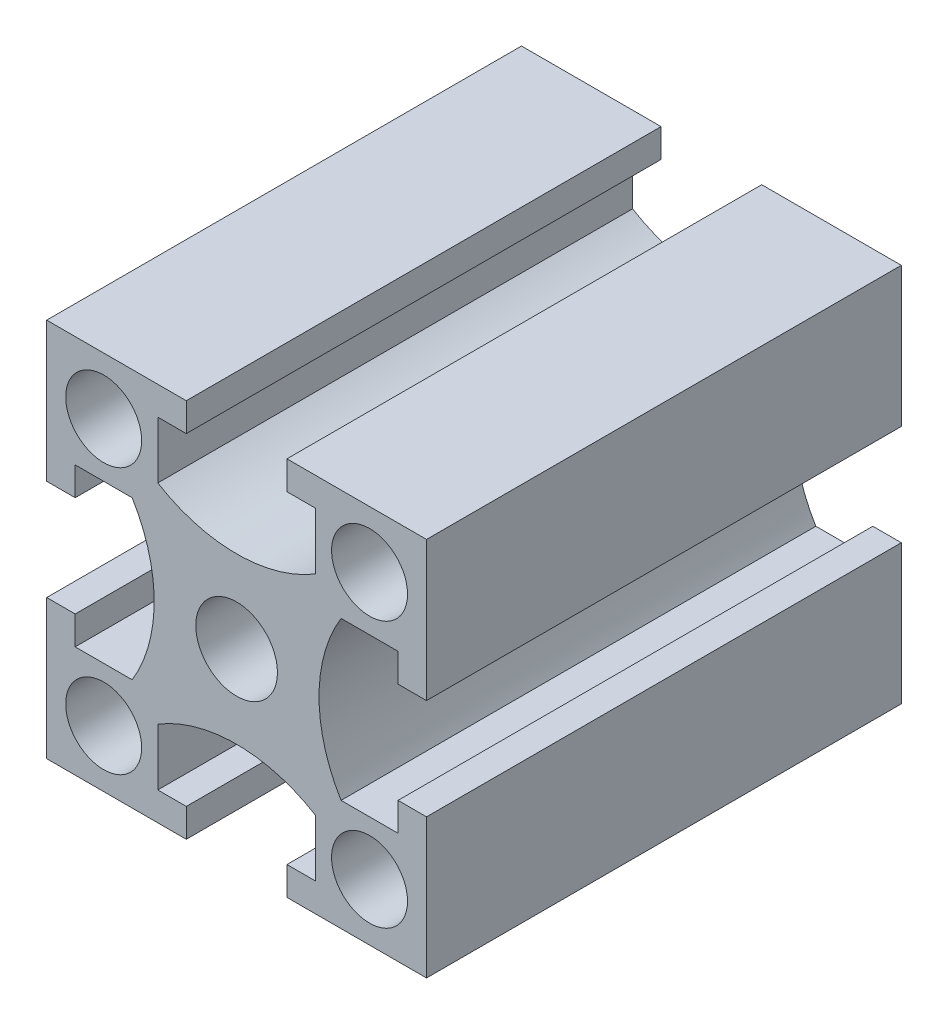
SolidWorks part; units mm, degrees
material "6061-T6 (SS)"
ref_plane "정면" through (0, 0, 0) normal (0, 0, 1) x (1, 0, 0)
ref_plane "윗면" through (0, 0, 0) normal (0, 1, 0) x (1, 0, 0)
ref_plane "우측면" through (0, 0, 0) normal (1, 0, 0) x (0, 0, -1)
sketch "스케치1" plane through (0, 0, 0) normal (0, 0, 1) x (1, 0, 0)
  line L1 (-10, 10) -> (10, 10)
  line L2 (-10, 10) -> (-10, -10)
  line L3 (-10, -10) -> (10, -10)
  line L4 (10, 10) -> (10, -10)
  line L5 (-10, 10) -> (10, -10) construction
  line L6 (-10, -10) -> (10, 10) construction
  point P0 (0, 0)
  dimension "D1" = 20
  dimension "D2" = 20
extrude "보스-돌출1" add sketch "스케치1" along normal blind 25
sketch "스케치2" plane through (0, 0, 25) normal (0, 0, 1) x (1, 0, 0)
  line L0 (-2.65, 10) -> (-2.65, 8.5)
  line L1 (10, 10) -> (-10, 10) construction
  line L2 (-2.65, 8.5) -> (-4.15, 8.5)
  line L3 (-4.15, 8.5) -> (-4.15, 5.5)
  line L4 (-2.65, 10) -> (2.65, 10)
  line L5 (2.65, 10) -> (2.65, 8.5)
  line L6 (2.65, 8.5) -> (4.15, 8.5)
  line L7 (4.15, 8.5) -> (4.15, 5.5)
  line L8 (10, 2.65) -> (8.5, 2.65)
  line L9 (8.5, 2.65) -> (8.5, 4.15)
  line L10 (8.5, 4.15) -> (5.5, 4.15)
  line L11 (10, 2.65) -> (10, -2.65)
  line L12 (10, -2.65) -> (8.5, -2.65)
  line L13 (8.5, -2.65) -> (8.5, -4.15)
  line L14 (8.5, -4.15) -> (5.5, -4.15)
  line L15 (2.65, -10) -> (2.65, -8.5)
  line L16 (2.65, -8.5) -> (4.15, -8.5)
  line L17 (4.15, -8.5) -> (4.15, -5.5)
  line L18 (2.65, -10) -> (-2.65, -10)
  line L19 (-2.65, -10) -> (-2.65, -8.5)
  line L20 (-2.65, -8.5) -> (-4.15, -8.5)
  line L21 (-4.15, -8.5) -> (-4.15, -5.5)
  line L22 (-10, -2.65) -> (-8.5, -2.65)
  line L23 (-8.5, -2.65) -> (-8.5, -4.15)
  line L24 (-8.5, -4.15) -> (-5.5, -4.15)
  line L25 (-10, -2.65) -> (-10, 2.65)
  line L26 (-10, 2.65) -> (-8.5, 2.65)
  line L27 (-8.5, 2.65) -> (-8.5, 4.15)
  line L28 (-8.5, 4.15) -> (-5.5, 4.15)
  arc A1 (-4.15, 5.5) -> (4.15, 5.5) centre (0, 12.3394) ccw
  arc A2 (5.5, 4.15) -> (5.5, -4.15) centre (12.3394, 0) ccw
  arc A3 (4.15, -5.5) -> (-4.15, -5.5) centre (0, -12.3394) ccw
  arc A4 (-5.5, -4.15) -> (-5.5, 4.15) centre (-12.3394, 0) ccw
  circle A5 centre (0, 0) radius 2.15
  circle A6 centre (-7, 7) radius 2
  circle A7 centre (7, 7) radius 2
  circle A8 centre (7, -7) radius 2
  circle A9 centre (-7, -7) radius 2
  point P4 (-2.65, 9.25)
  point P43 (0, 0)
  dimension "D2" = 1.5
  dimension "D8" = 4.3
  dimension "D9" = 4
  dimension "D10" = 4
  dimension "D11" = 4
  dimension "D12" = 4
  dimension "D21" = 8
  dimension "D1" = 5.3
  dimension "D3" = 8.3
  dimension "D4" = 4.15
  dimension "D5" = 2.65
  dimension "D6" = 4
  dimension "D7" = 3
  dimension "D13" = 14
  dimension "D14" = 7
  dimension "D15" = 7
  dimension "D16" = 7
  dimension "D17" = 14
  dimension "D18" = 7
  dimension "D19" = 7
  dimension "D20" = 7
extrude "컷-돌출1" cut sketch "스케치2" against normal blind 300
